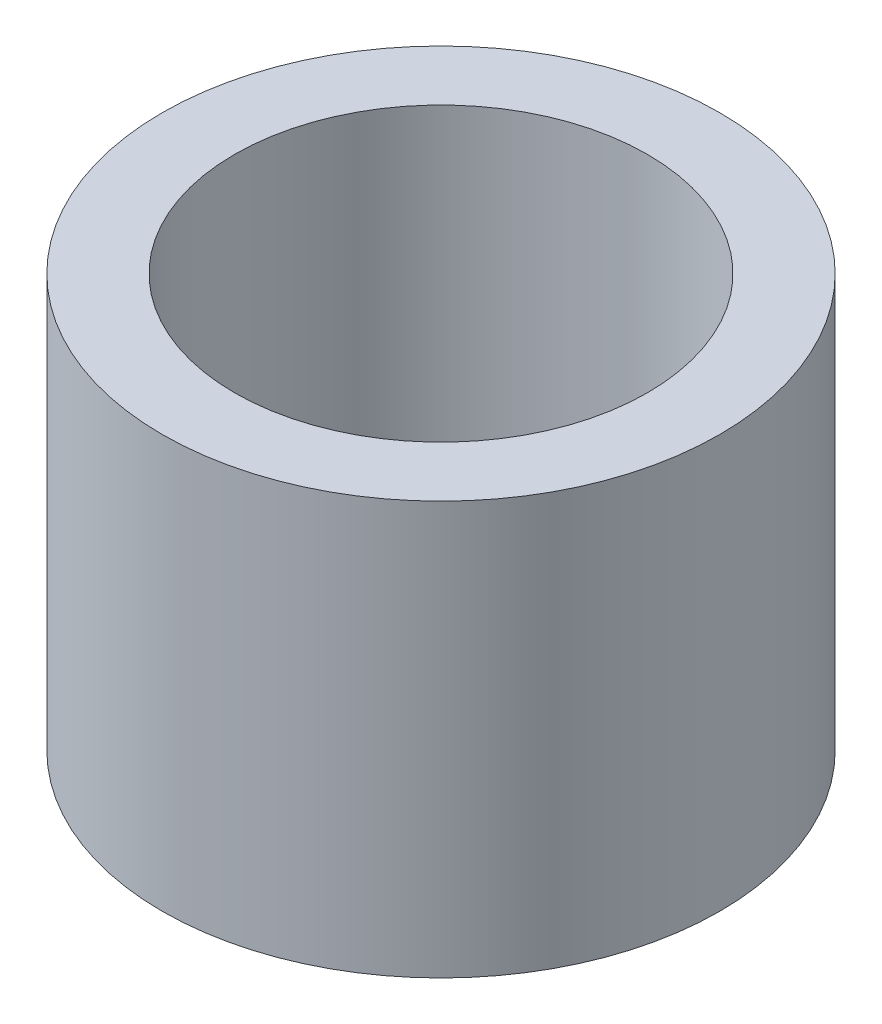
SolidWorks part; units mm, degrees
ref_plane "Front Plane" through (0, 0, 0) normal (0, 0, 1) x (1, 0, 0)
ref_plane "Top Plane" through (0, 0, 0) normal (0, 1, 0) x (1, 0, 0)
ref_plane "Right Plane" through (0, 0, 0) normal (1, 0, 0) x (0, 0, -1)
sketch "Sketch1" plane through (0, 0, 0) normal (0, 1, 0) x (1, 0, 0)
  circle A0 centre (0, 0) radius 6.35
  circle A1 centre (0, 0) radius 8.5725
  dimension "D1" = 12.7
  dimension "D2" = 17.145
extrude "Boss-Extrude1" add sketch "Sketch1" along normal blind 12.7
